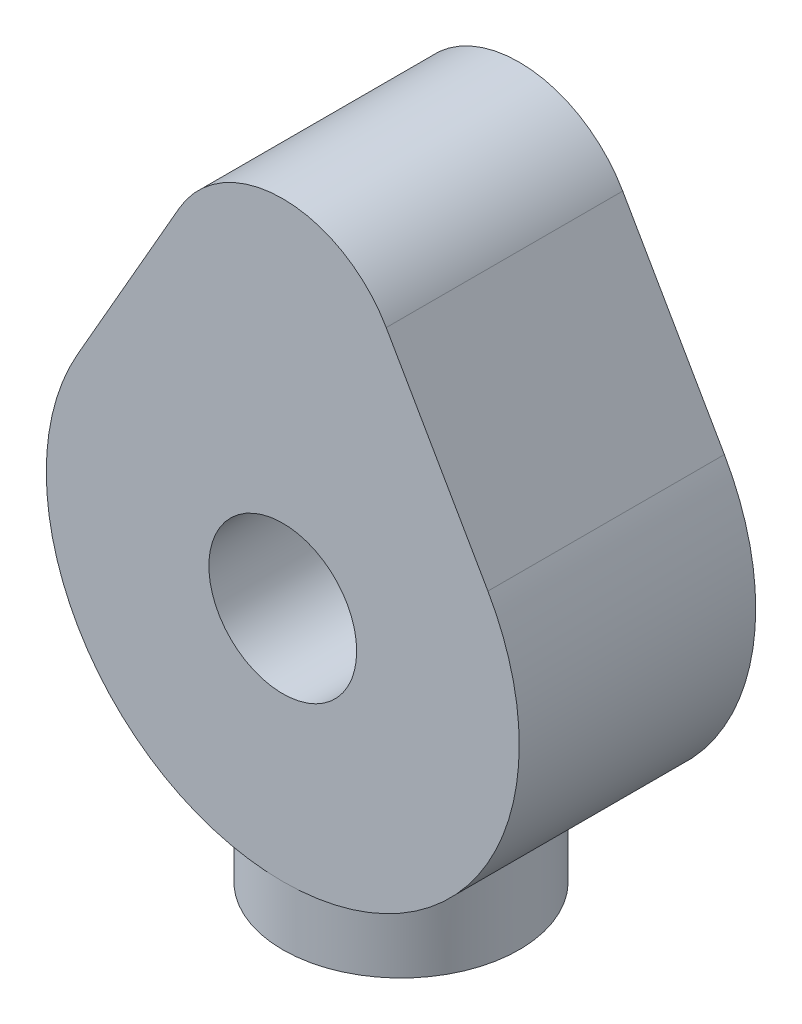
SolidWorks part; units mm, degrees
ref_plane "Plan de face" through (0, 0, 0) normal (0, 0, 1) x (1, 0, 0)
ref_plane "Plan de dessus" through (0, 0, 0) normal (0, 1, 0) x (1, 0, 0)
ref_plane "Plan de droite" through (0, 0, 0) normal (1, 0, 0) x (0, 0, -1)
sketch "Esquisse1" plane through (0, 0, 0) normal (0, 0, 1) x (1, 0, 0)
  line L0 (-17.5, 49.8961) -> (-34.7008, 19.8961)
  line L1 (17.5, 49.8961) -> (34.7008, 19.8961)
  line L2 (-34.7008, 19.8961) -> (34.7008, 19.8961) construction
  line L3 (-17.5, 49.8961) -> (17.5, 49.8961) construction
  line L4 (0, 49.8961) -> (0, 19.8961) construction
  arc A0 (-17.5, 49.8961) -> (17.5, 49.8961) centre (0, 39.8623) cw
  arc A1 (-34.7008, 19.8961) -> (34.7008, 19.8961) centre (0, 0) ccw
  dimension "D1" = 40
  dimension "D2" = 30
  dimension "D3" = 35
extrude "Boss.-Extru.1" add sketch "Esquisse1" along normal mid plane 40
sketch "Esquisse2" plane through (0, 0, 0) normal (0, 1, 0) x (1, 0, 0)
  line L0 (-40, -20) -> (40, -20) construction
  line L1 (40, 20) -> (-40, 20) construction
  circle A0 centre (0, 0) radius 20
extrude "Boss.-Extru.2" add sketch "Esquisse2" against normal blind 50
sketch "Esquisse3" plane through (0, 0, 20) normal (0, 0, 1) x (1, 0, 0)
  circle A0 centre (0, 0) radius 12.5
  dimension "D1" = 25
extrude "Enlèv. mat.-Extru.1" cut sketch "Esquisse3" against normal through all
sketch "Esquisse5" plane through (0, 0, 0) normal (0, 0, 1) x (1, 0, 0)
  line L0 (0, -50) -> (0, -20)
  line L1 (-20, -50) -> (20, -50) construction
  line L2 (0, -20) -> (10, -25.7735)
  line L3 (10, -25.7735) -> (10, -50)
  line L4 (10, -50) -> (0, -50)
  line L5 (0, -50) -> (0.4443, -49.9593)
  dimension "D1" = 60
  dimension "D2" = 10
  dimension "D3" = 30
revolve "Enlèvement de matière-Révolution1" cut sketch "Esquisse5" angle 360 about L0
